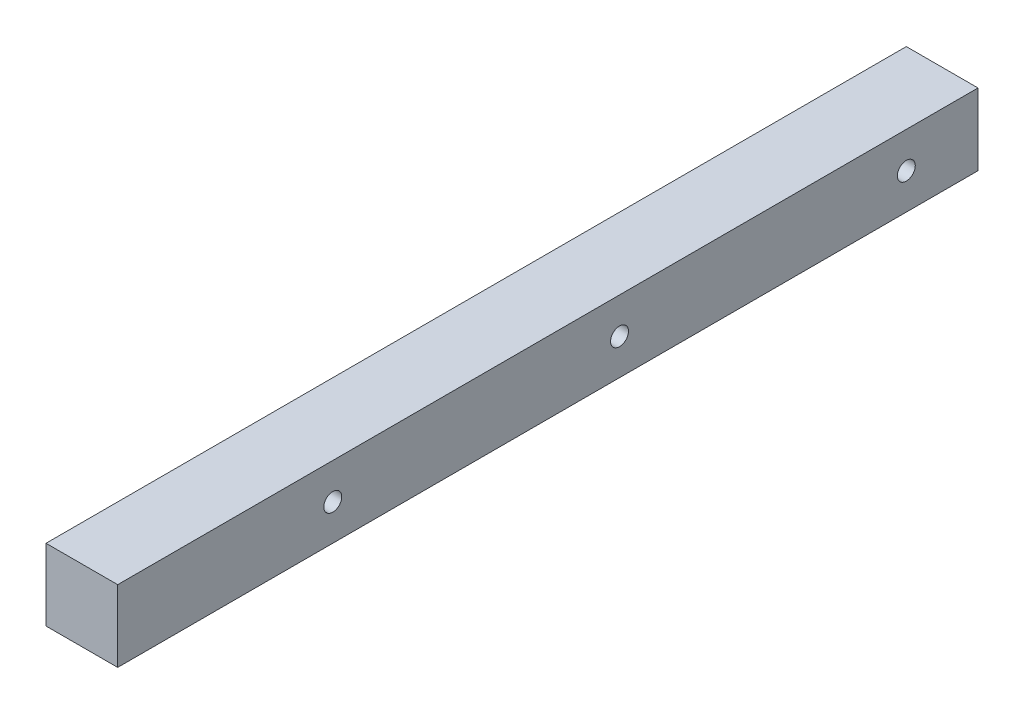
SolidWorks part; units mm, degrees
ref_plane "Front Plane" through (0, 0, 0) normal (0, 0, 1) x (1, 0, 0)
ref_plane "Top Plane" through (0, 0, 0) normal (0, 1, 0) x (1, 0, 0)
ref_plane "Right Plane" through (0, 0, 0) normal (1, 0, 0) x (0, 0, -1)
sketch "Sketch7" plane through (0, 0, 0) normal (0, 0, 1) x (1, 0, 0)
  line L1 (-12.7, -12.7) -> (12.7, -12.7)
  line L2 (-12.7, -12.7) -> (-12.7, 12.7)
  line L3 (-12.7, 12.7) -> (12.7, 12.7)
  line L4 (12.7, -12.7) -> (12.7, 12.7)
  line L5 (-12.7, -12.7) -> (12.7, 12.7) construction
  line L6 (-12.7, 12.7) -> (12.7, -12.7) construction
  point P0 (0, 0)
  dimension "D1" = 25.4
extrude "Boss-Extrude3" add sketch "Sketch7" along normal mid plane 304.8
sketch "Sketch9" plane through (12.7, 0, 0) normal (-1, 0, 0) x (0, -1, 0)
  circle A0 centre (0, -25.4) radius 3.175
  point P3 (0, 27.0679)
  point P5 (0, 0)
  dimension "D1" = 6.35
  dimension "D2" = 25.4
extrude "Cut-Extrude1" cut sketch "Sketch9" along normal through all
pattern_linear "LPattern1" count 2 spacing 101.6 along (0, 0, -1) count 2 spacing 101.6 along (0, 0, 1) of "Cut-Extrude1"
